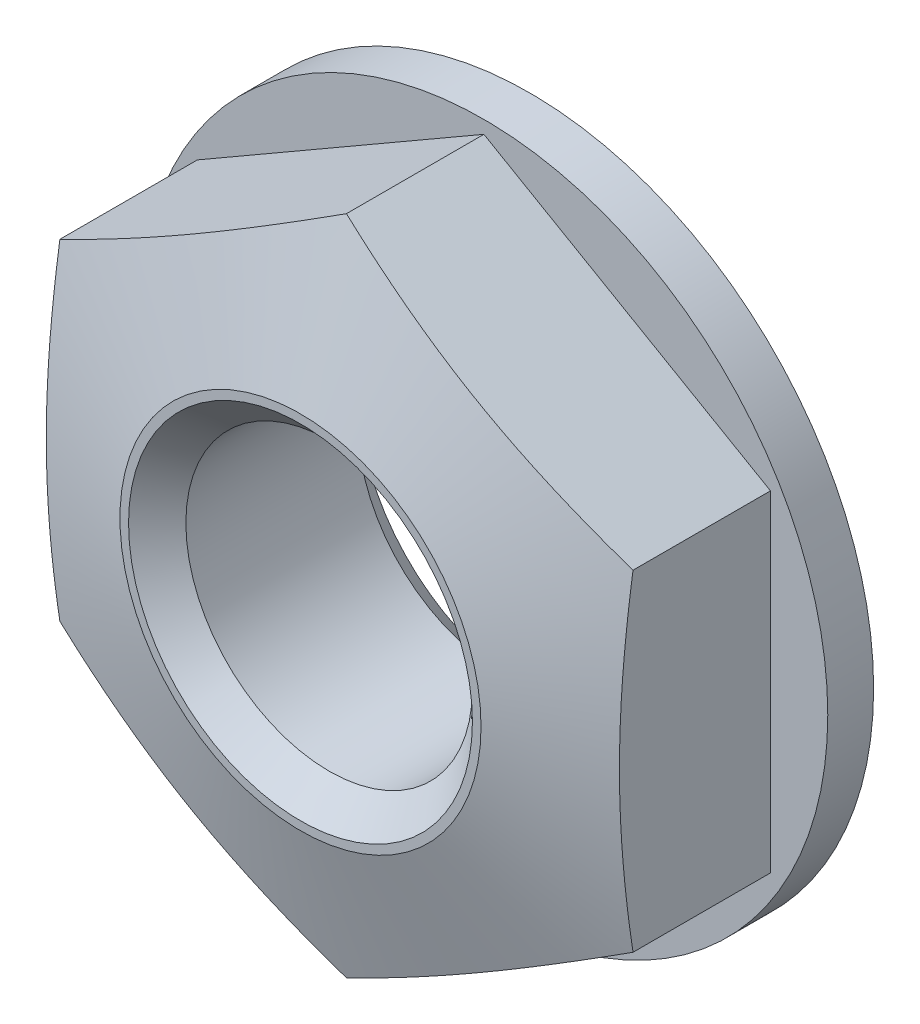
SolidWorks part; units mm, degrees
ref_plane "Спереди" through (0, 0, 0) normal (0, 0, 1) x (1, 0, 0)
ref_plane "Сверху" through (0, 0, 0) normal (0, 1, 0) x (1, 0, 0)
ref_plane "Справа" through (0, 0, 0) normal (1, 0, 0) x (0, 0, -1)
sketch "Эскиз1" plane through (0, 0, 0) normal (0, 0, 1) x (1, 0, 0)
  circle A1 centre (0, 0) radius 6
  dimension "D2" = 12
extrude "Бобышка-Вытянуть1" add sketch "Эскиз1" along normal blind 0.8
sketch "Эскиз2" plane through (0, 0, 0.8) normal (0, 0, 1) x (1, 0, 0)
  line L1 (0, 5.7735) -> (-5, 2.8868)
  line L2 (-5, 2.8868) -> (-5, -2.8868)
  line L3 (-5, -2.8868) -> (0, -5.7735)
  line L4 (0, -5.7735) -> (5, -2.8868)
  line L5 (5, -2.8868) -> (5, 2.8868)
  line L6 (5, 2.8868) -> (0, 5.7735)
  circle A0 centre (0, 0) radius 5 construction
  dimension "D1" = 10
extrude "Бобышка-Вытянуть2" add sketch "Эскиз2" along normal blind 3.2
sketch "Эскиз3" plane through (0, 0, 4) normal (0, 0, 1) x (1, 0, 0)
  circle A0 centre (0, 0) radius 3.15
  dimension "D1" = 6.3
extrude "Вырез-Вытянуть1" cut sketch "Эскиз3" against normal blind 3.2 draft 73 flip side to cut
hole_wizard "Отверстие обработанное метчиком M61" positions "Эскиз4" profile "Эскиз5" tap size "M6" standard "ISO" end condition through all
sketch "Эскиз4" plane through (0, 0, 4) normal (0, 0, 1) x (1, 0, 0)
  point P0 (0, 0)
sketch "Эскиз5" plane through (0, 0, 4) normal (1, 0, 0) x (0, -1, 0)
  line L0 (0, 0) -> (0, 4)
  line L1 (0, 4) -> (2.5, 4)
  line L2 (2.5, 4) -> (2.5, 0)
  line L5 (2.5, 0) -> (0, 0)
  line L11 (0, -6.35) -> (0, 107.95) construction
  dimension "Диаметр проходного сверла" = 5
  dimension "Глубина проходного сверла" = 4
cosmetic thread "Отверстие резьбы1" parameters "D2"=6
chamfer "Фаска1" distance 0.5 1 edges at (2.5, 0, 4)
chamfer "Фаска2" distance 0.5 1 edges at (2.5, 0, 0)
